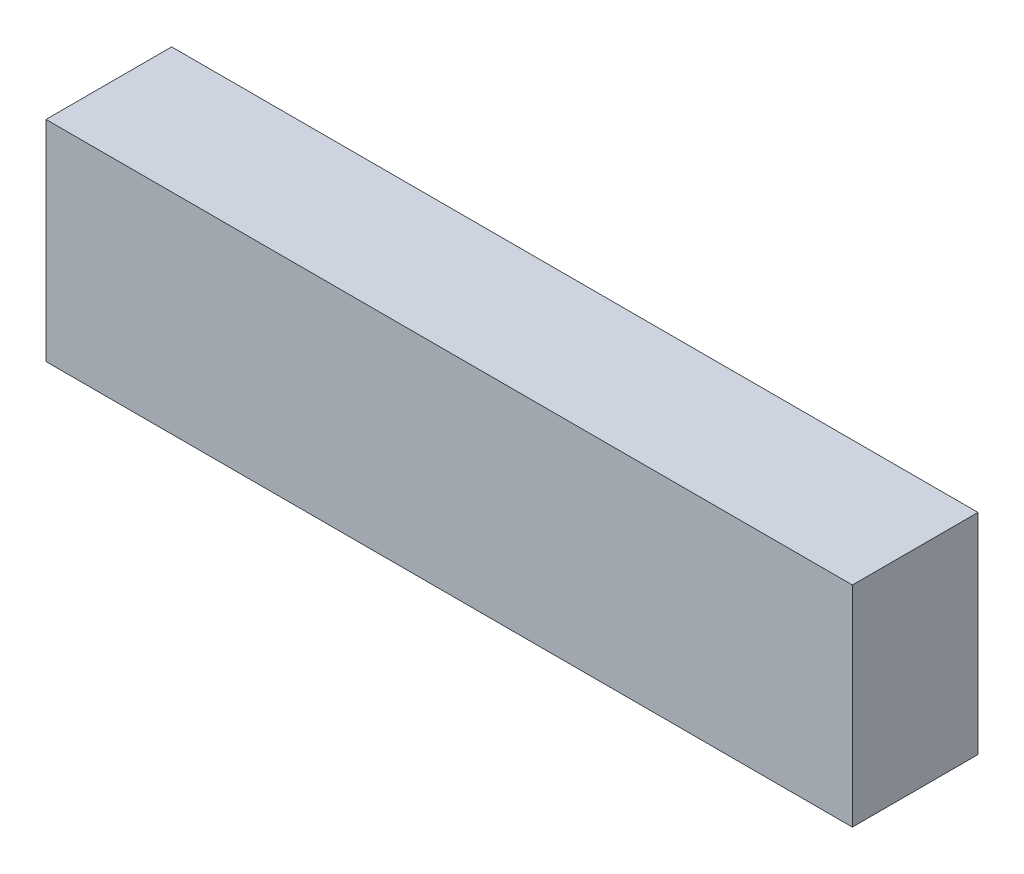
SolidWorks part; units mm, degrees
ref_plane "Front Plane" through (0, 0, 0) normal (0, 0, 1) x (1, 0, 0)
ref_plane "Top Plane" through (0, 0, 0) normal (0, 1, 0) x (1, 0, 0)
ref_plane "Right Plane" through (0, 0, 0) normal (1, 0, 0) x (0, 0, -1)
sketch "Sketch1" plane through (0, 0, 0) normal (0, 0, 1) x (1, 0, 0)
  line L0 (79.2368, 77.7714) -> (32.3045, 77.7714) construction
  line L1 (32.5045, 77.5714) -> (79.0368, 77.5714)
  line L2 (32.5045, 77.5714) -> (32.5045, 65.47)
  line L3 (32.5045, 65.47) -> (79.0368, 65.47)
  line L4 (79.0368, 77.5714) -> (79.0368, 65.47)
  line L5 (79.2368, 65.27) -> (79.2368, 77.7714) construction
  line L6 (79.2368, 65.27) -> (32.3045, 65.27) construction
  line L7 (32.3045, 65.27) -> (32.3045, 77.7714) construction
  dimension "D1" = 0.2
  dimension "D2" = 0.2
  dimension "D3" = 0.2
  dimension "D4" = 0.2
extrude "Boss-Extrude1" add sketch "Sketch1" along normal blind 7.25 contours L1 L4 L3 L2
shell "Shell1" thickness 0.5
equation "\"D2@Sketch1\"=\"D1@Sketch1\""
equation "\"D3@Sketch1\"=\"D1@Sketch1\""
equation "\"D4@Sketch1\"=\"D1@Sketch1\""
